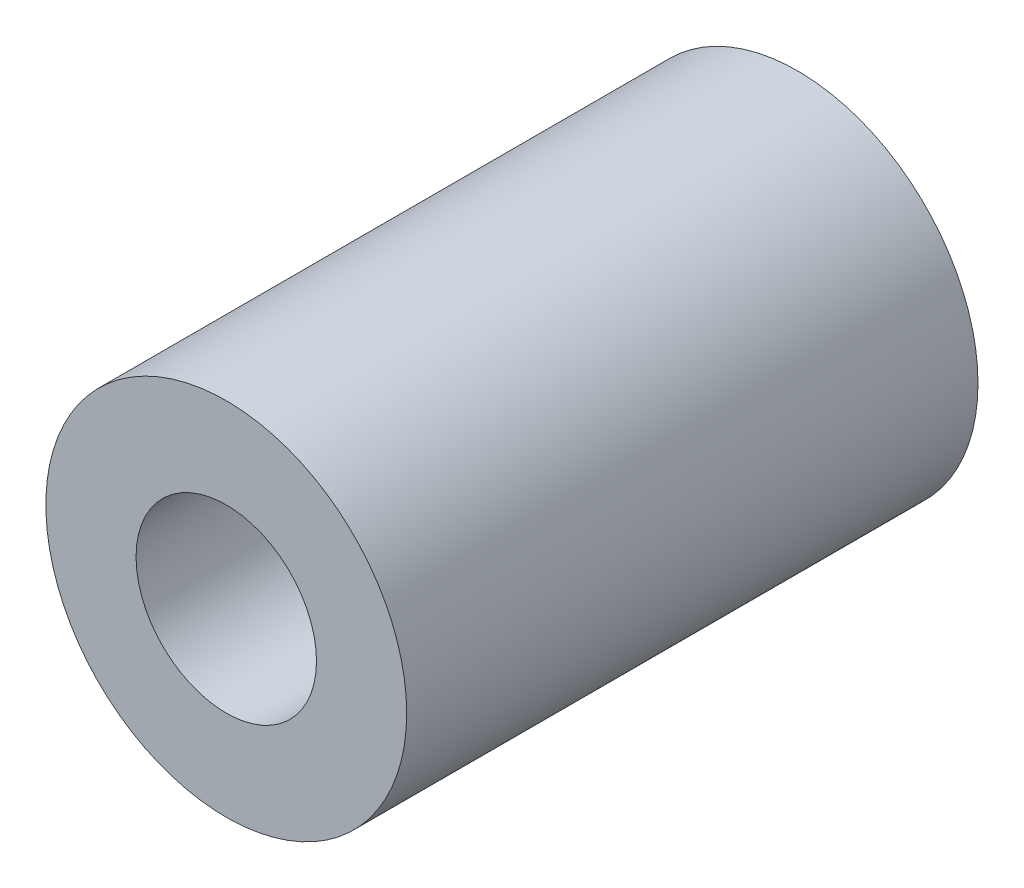
SolidWorks part; units mm, degrees
ref_plane "前视基准面" through (0, 0, 0) normal (0, 0, 1) x (1, 0, 0)
ref_plane "上视基准面" through (0, 0, 0) normal (0, 1, 0) x (1, 0, 0)
ref_plane "右视基准面" through (0, 0, 0) normal (1, 0, 0) x (0, 0, -1)
sketch "草图1" plane through (0, 0, 0) normal (0, 0, 1) x (1, 0, 0)
  circle A0 centre (0, 0) radius 3
  circle A1 centre (0, 0) radius 6
extrude "凸台-拉伸1" add sketch "草图1" along normal blind 19
